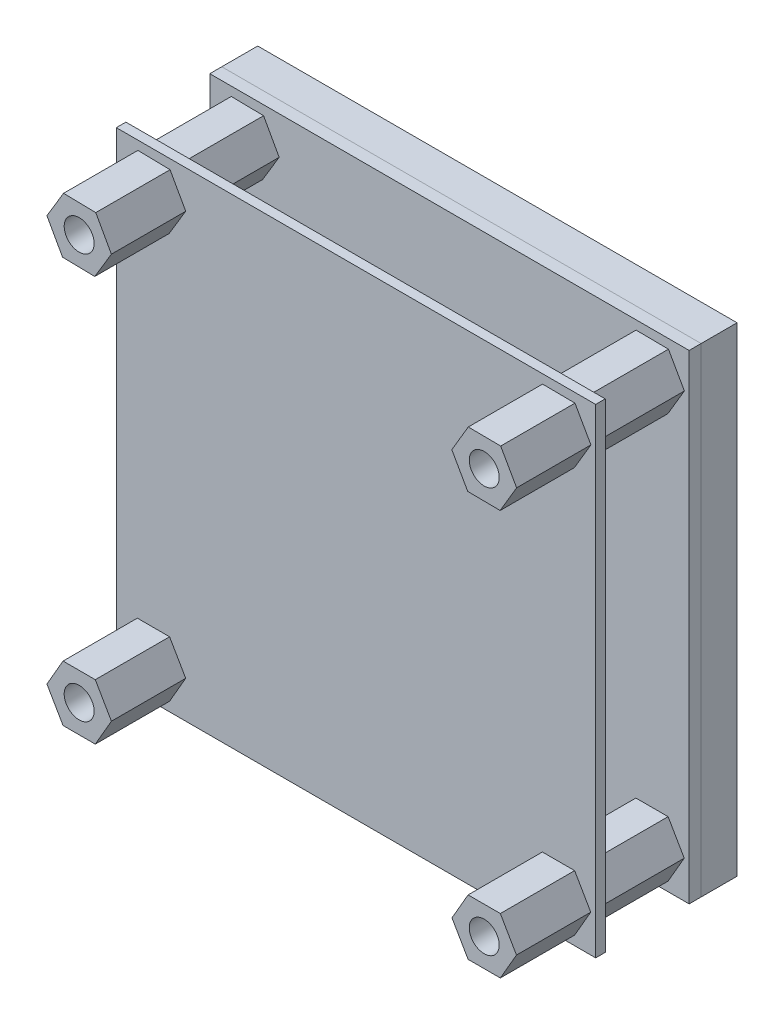
SolidWorks part; units mm, degrees
ref_plane "Front Plane" through (0, 0, 0) normal (0, 0, 1) x (1, 0, 0)
ref_plane "Top Plane" through (0, 0, 0) normal (0, 1, 0) x (1, 0, 0)
ref_plane "Right Plane" through (0, 0, 0) normal (1, 0, 0) x (0, 0, -1)
sketch "Sketch1" plane through (0, 0, 0) normal (0, 0, 1) x (1, 0, 0)
  line L1 (-20, 20) -> (20, 20)
  line L2 (-20, 20) -> (-20, -20)
  line L3 (-20, -20) -> (20, -20)
  line L4 (20, 20) -> (20, -20)
  line L5 (-20, 20) -> (20, -20) construction
  line L6 (-20, -20) -> (20, 20) construction
  point P0 (0, 0)
extrude "Boss-Extrude1" add sketch "Sketch1" along normal blind 3
sketch "Sketch2" plane through (0, 0, 3) normal (0, 0, 1) x (1, 0, 0)
  line L1 (-20, 20) -> (20, 20)
  line L2 (-20, 20) -> (-20, -20)
  line L3 (-20, -20) -> (20, -20)
  line L4 (20, 20) -> (20, -20)
  line L5 (-20, 20) -> (20, -20) construction
  line L6 (-20, -20) -> (20, 20) construction
  point P0 (0, 0)
extrude "Boss-Extrude2" add sketch "Sketch2" along normal blind 1 separate body
sketch "Sketch3" plane through (0, 0, 4) normal (0, 0, 1) x (1, 0, 0)
  line L0 (-20, 20) -> (-20, -20) construction
  line L1 (20, 20) -> (-20, 20) construction
  line L2 (20, -20) -> (20, 20) construction
  line L3 (-20, -20) -> (20, -20) construction
  line L5 (-15.5976, 14.5458) -> (-14.21, 16.8508)
  line L6 (-14.21, 16.8508) -> (-15.5124, 19.205)
  line L7 (-15.5124, 19.205) -> (-18.2024, 19.2542)
  line L8 (-18.2024, 19.2542) -> (-19.59, 16.9492)
  line L9 (-19.59, 16.9492) -> (-18.2876, 14.595)
  line L10 (-18.2876, 14.595) -> (-15.5976, 14.5458)
  line L11 (18.2289, 14.5458) -> (19.6033, 16.8738)
  line L12 (19.6033, 16.8738) -> (18.2743, 19.228)
  line L13 (18.2743, 19.228) -> (15.5711, 19.2542)
  line L14 (15.5711, 19.2542) -> (14.1967, 16.9262)
  line L15 (14.1967, 16.9262) -> (15.5257, 14.572)
  line L16 (15.5257, 14.572) -> (18.2289, 14.5458)
  line L17 (19.5905, -16.9) -> (18.2452, -14.57)
  line L18 (18.2452, -14.57) -> (15.5548, -14.57)
  line L19 (15.5548, -14.57) -> (14.2095, -16.9)
  line L20 (14.2095, -16.9) -> (15.5548, -19.23)
  line L21 (15.5548, -19.23) -> (18.2452, -19.23)
  line L22 (18.2452, -19.23) -> (19.5905, -16.9)
  line L23 (-14.2095, -16.9) -> (-15.5548, -14.57)
  line L24 (-15.5548, -14.57) -> (-18.2452, -14.57)
  line L25 (-18.2452, -14.57) -> (-19.5905, -16.9)
  line L26 (-19.5905, -16.9) -> (-18.2452, -19.23)
  line L27 (-18.2452, -19.23) -> (-15.5548, -19.23)
  line L28 (-15.5548, -19.23) -> (-14.2095, -16.9)
  circle A0 centre (-16.9, 16.9) radius 1.25
  circle A1 centre (16.9, 16.9) radius 1.25
  circle A2 centre (16.9, -16.9) radius 1.25
  circle A3 centre (-16.9, -16.9) radius 1.25
  circle A4 centre (-16.9, 16.9) radius 2.33 construction
  circle A5 centre (16.9, 16.9) radius 2.3412 construction
  circle A6 centre (16.9, -16.9) radius 2.33 construction
  circle A7 centre (-16.9, -16.9) radius 2.33 construction
  dimension "D5" = 2.5
  dimension "D6" = 2.5
  dimension "D7" = 2.5
  dimension "D8" = 2.5
  dimension "D1" = 3.1
  dimension "D2" = 3.1
  dimension "D3" = 3.1
  dimension "D4" = 3.1
extrude "Boss-Extrude3" add sketch "Sketch3" along normal blind 14 separate body
ref_plane "Plane1" through (0, 0, 11) normal (0, 0, 1) x (1, 0, 0)
sketch "Sketch4" plane through (0, 0, 11) normal (0, 0, 1) x (1, 0, 0)
  line L1 (-20, 20) -> (20, 20)
  line L2 (-20, 20) -> (-20, -20)
  line L3 (-20, -20) -> (20, -20)
  line L4 (20, 20) -> (20, -20)
  line L5 (-20, 20) -> (20, -20) construction
  line L6 (-20, -20) -> (20, 20) construction
  point P0 (0, 0)
extrude "Boss-Extrude4" add sketch "Sketch4" along normal blind 0.8
